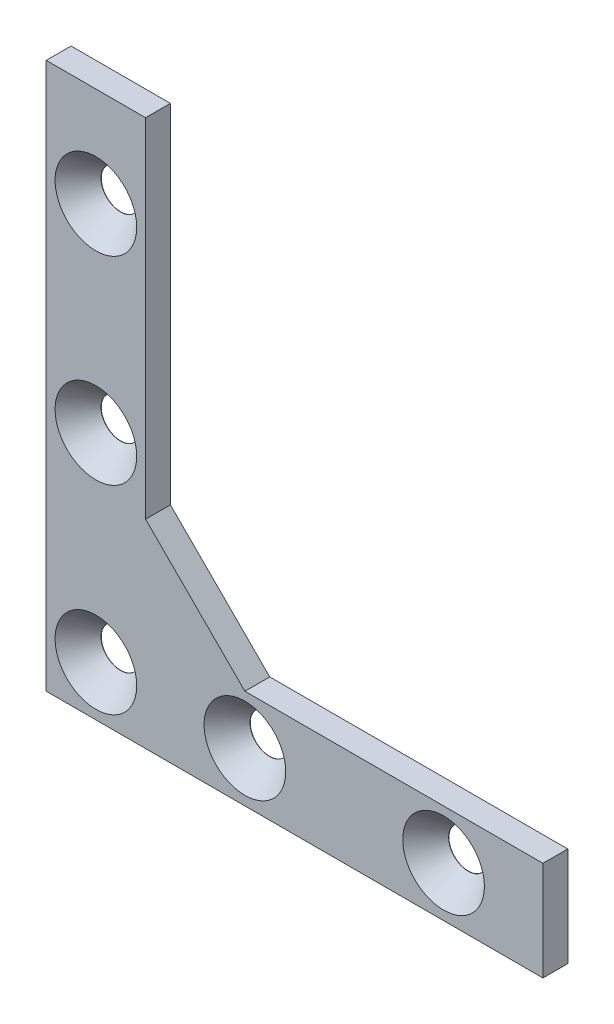
SolidWorks part; units mm, degrees
ref_plane "Front Plane" through (0, 0, 0) normal (0, 0, 1) x (1, 0, 0)
ref_plane "Top Plane" through (0, 0, 0) normal (0, 1, 0) x (1, 0, 0)
ref_plane "Right Plane" through (0, 0, 0) normal (1, 0, 0) x (0, 0, -1)
sketch "Sketch1" plane through (0, 0, 0) normal (0, 0, 1) x (1, 0, 0)
  line L1 (-273.4534, -6.35) -> (-273.4534, 63.5)
  line L2 (-273.4534, 63.5) -> (-260.7534, 63.5)
  line L3 (-273.4534, -6.35) -> (-209.9534, -6.35)
  line L10 (-260.7534, 19.05) -> (-260.7534, 63.5)
  line L11 (-209.9534, -6.35) -> (-209.9534, 6.35)
  line L12 (-209.9534, 6.35) -> (-248.0534, 6.35)
  line L13 (-248.0534, 6.35) -> (-260.7534, 19.05)
  dimension "D1" = 69.85
  dimension "D2" = 63.5
  dimension "D5" = 12.7
  dimension "D6" = 44.45
extrude "Boss-Extrude1" add sketch "Sketch1" along normal blind 3.175
sketch "Sketch2" plane through (0, 0, 3.175) normal (0, 0, 1) x (1, 0, 0)
  line L0 (-267.1034, 63.5) -> (-267.1034, 50.8) construction
  line L1 (-260.7534, 63.5) -> (-273.4534, 63.5) construction
  line L2 (-267.1034, 50.8) -> (-267.1034, 25.4382) construction
  line L3 (-267.1034, 0.0382) -> (-248.0534, 0.0382) construction
  line L4 (-267.1034, 25.4382) -> (-267.1034, 0.0382) construction
  line L5 (-248.0534, 0.0382) -> (-222.6534, 0.0382) construction
  line L6 (-209.7517, 0) -> (-222.6534, 0.0382) construction
  dimension "D1" = 25.4
  dimension "D2" = 19.05
  dimension "D3" = 25.4
hole_wizard "#10 Clearance Hole1" positions "Sketch3" profile "Sketch4" hole size "#10" standard "ANSI Inch" end condition through all
sketch "Sketch3" plane through (0, 0, 3.175) normal (0, 0, 1) x (1, 0, 0)
  point P0 (-267.1034, 0.0382)
  point P3 (-267.1034, 25.4382)
  point P6 (-267.1034, 50.8)
  point P9 (-248.0534, 0.0382)
  point P12 (-222.6534, 0.0382)
sketch "Sketch4" plane through (-267.1034, 0.0382, 3.175) normal (1, 0, 0) x (0, -1, 0)
  line L0 (0, 0) -> (0, 3.175)
  line L1 (0, 3.175) -> (2.4892, 3.175)
  line L2 (2.4892, 3.175) -> (2.4892, 3.1411)
  line L3 (2.4892, 3.1411) -> (5.2197, 0)
  line L5 (5.2197, 0) -> (0, 0)
  line L6 (-2.4892, 3.1411) -> (-5.2197, 0) construction
  line L11 (0, -6.35) -> (0, 107.95) construction
  dimension "Thru Hole Dia." = 4.9784
  dimension "Thru Hole Depth" = 3.175
  dimension "Near C'Sink Dia." = 10.4394
  dimension "Near C'Sink Angle" = 82
